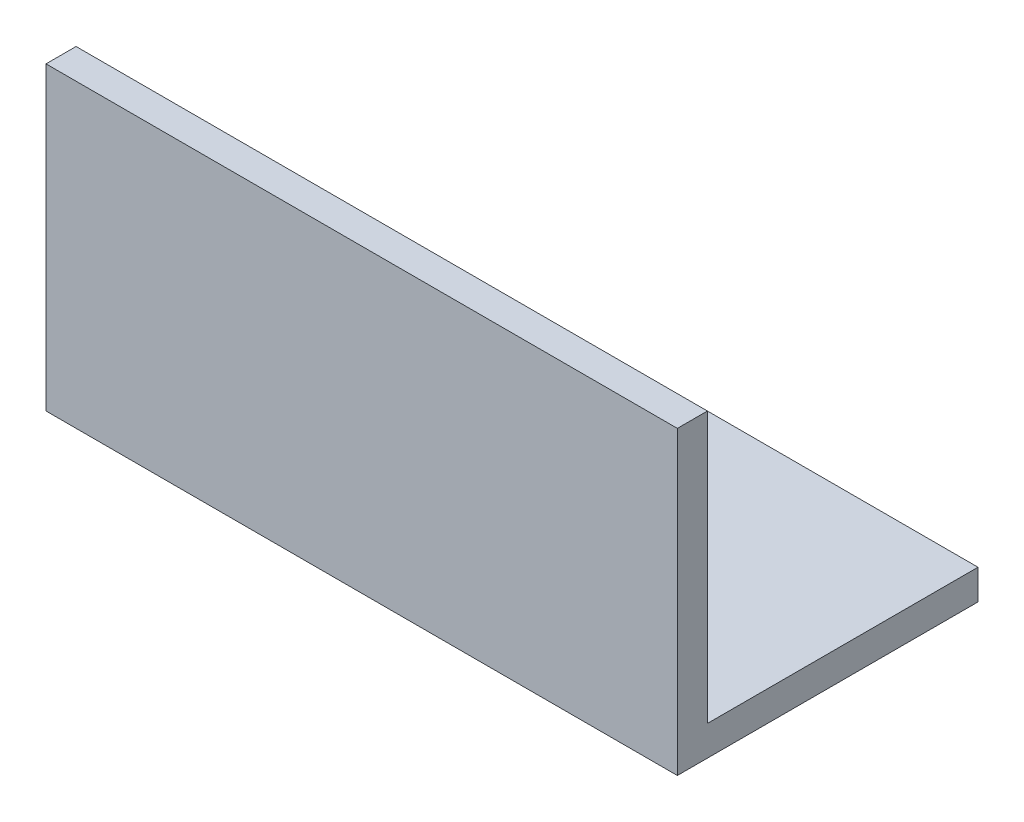
SolidWorks part; units mm, degrees
ref_plane "Front Plane" through (0, 0, 0) normal (0, 0, 1) x (1, 0, 0)
ref_plane "Top Plane" through (0, 0, 0) normal (0, 1, 0) x (1, 0, 0)
ref_plane "Right Plane" through (0, 0, 0) normal (1, 0, 0) x (0, 0, -1)
sketch "Sketch1" plane through (0, 0, 0) normal (1, 0, 0) x (0, 0, -1)
  line L0 (0, 20) -> (0, 0)
  line L1 (0, 0) -> (20, 0)
  line L2 (20, 0) -> (20, 2)
  line L3 (20, 2) -> (2, 2)
  line L4 (2, 2) -> (2, 20)
  line L5 (2, 20) -> (0, 20)
  dimension "D1" = 20
  dimension "D2" = 20
  dimension "D3" = 2
  dimension "D4" = 2
extrude "Boss-Extrude1" add sketch "Sketch1" against normal blind 42
